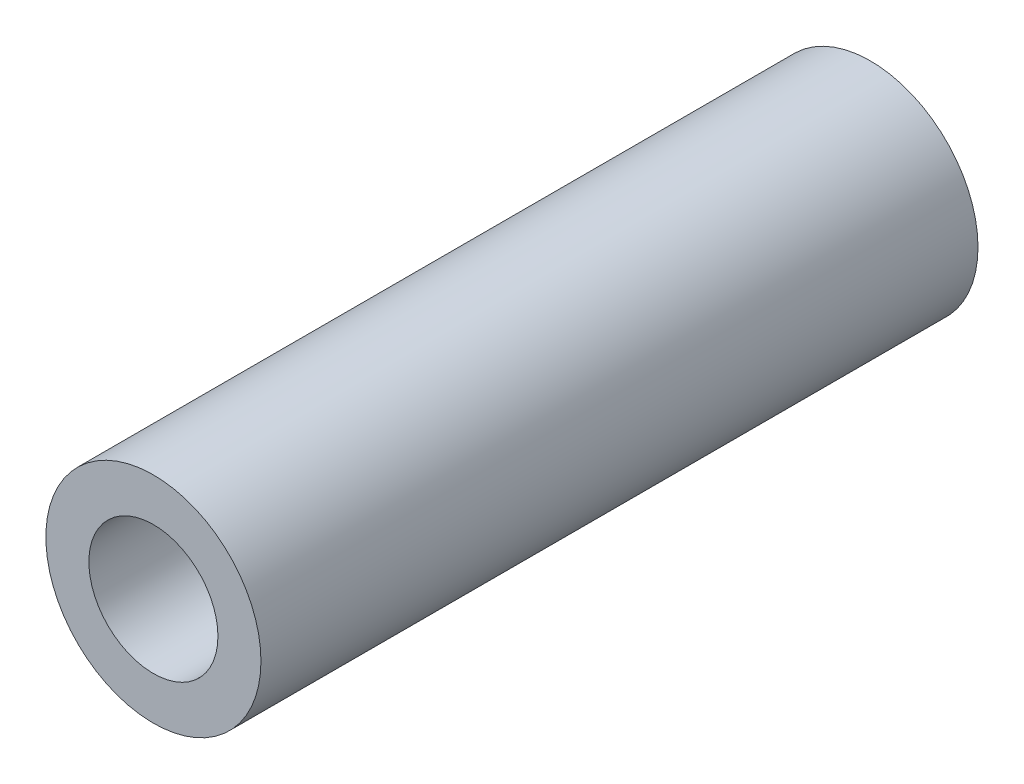
SolidWorks part; units mm, degrees
ref_plane "前视基准面" through (0, 0, 0) normal (0, 0, 1) x (1, 0, 0)
ref_plane "上视基准面" through (0, 0, 0) normal (0, 1, 0) x (1, 0, 0)
ref_plane "右视基准面" through (0, 0, 0) normal (1, 0, 0) x (0, 0, -1)
sketch "草图1" plane through (0, 0, 0) normal (0, 0, 1) x (1, 0, 0)
  circle A0 centre (0, 0) radius 7.5
  circle A1 centre (0, 0) radius 4.5
  dimension "D1" = 15
  dimension "D2" = 9
extrude "凸台-拉伸1" add sketch "草图1" along normal blind 50
